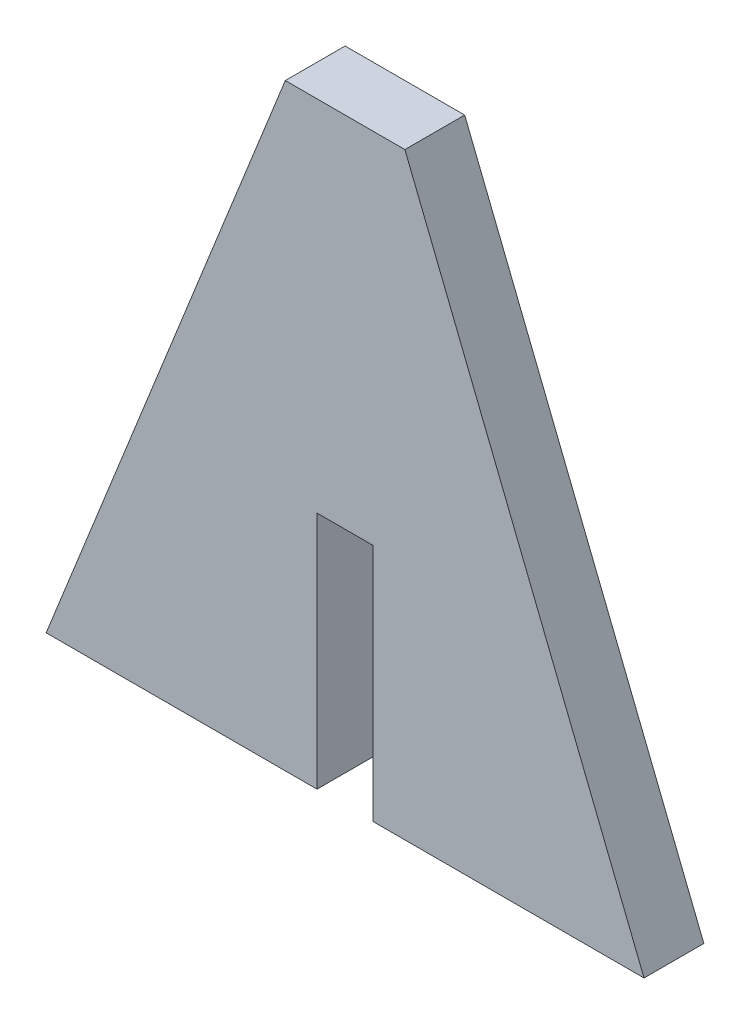
SolidWorks part; units mm, degrees
ref_plane "정면" through (0, 0, 0) normal (0, 0, 1) x (1, 0, 0)
ref_plane "윗면" through (0, 0, 0) normal (0, 1, 0) x (1, 0, 0)
ref_plane "우측면" through (0, 0, 0) normal (1, 0, 0) x (0, 0, -1)
sketch "스케치1" plane through (0, 0, 0) normal (0, 0, 1) x (1, 0, 0)
  line L1 (-5, 25) -> (5, 25)
  line L2 (-5, 25) -> (-25, -25)
  line L3 (-25, -25) -> (25, -25)
  line L4 (5, 25) -> (25, -25)
  line L5 (-2.35, -25) -> (2.35, -25)
  line L6 (-2.35, -25) -> (-2.35, -5)
  line L7 (-2.35, -5) -> (2.35, -5)
  line L8 (2.35, -25) -> (2.35, -5)
  point P0 (0, 25)
  point P6 (0, -5)
  point P7 (0, -25)
  point P8 (-15, 0)
  point P9 (15, 0)
  dimension "D1" = 50
  dimension "D2" = 50
  dimension "D3" = 10
  dimension "D4" = 4.7
  dimension "D5" = 20
extrude "보스-돌출1" add sketch "스케치1" along normal blind 5 contours L8 L3 L4 L1 L2 L6 L7
